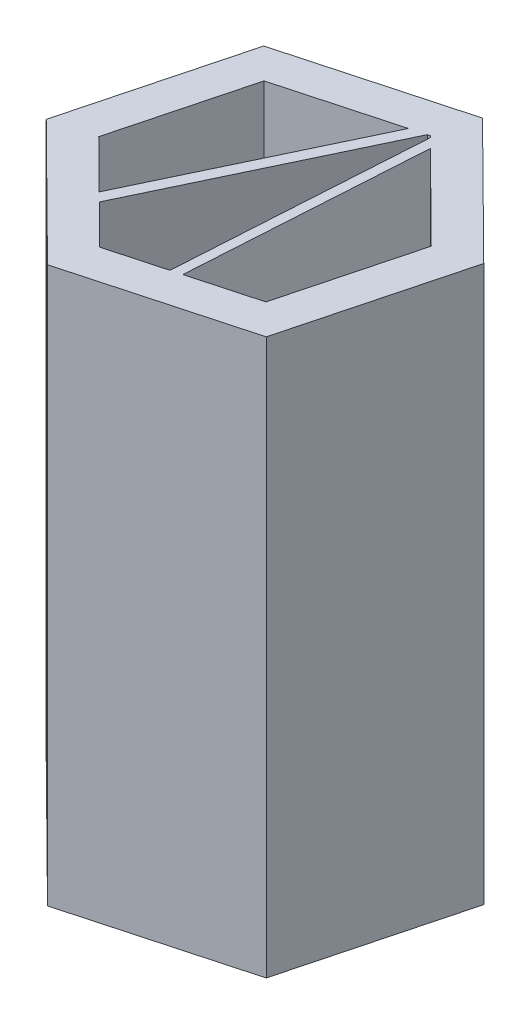
SolidWorks part; units mm, degrees
ref_plane "Front Plane" through (0, 0, 0) normal (0, 0, 1) x (1, 0, 0)
ref_plane "Top Plane" through (0, 0, 0) normal (0, 1, 0) x (1, 0, 0)
ref_plane "Right Plane" through (0, 0, 0) normal (1, 0, 0) x (0, 0, -1)
sketch "Sketch1" plane through (0, 0, 0) normal (0, 1, 0) x (1, 0, 0)
  line L1 (10.2574, -10.1548) -> (13.923, 3.8057)
  line L2 (13.923, 3.8057) -> (3.6656, 13.9605)
  line L3 (3.6656, 13.9605) -> (-10.2574, 10.1548)
  line L4 (-10.2574, 10.1548) -> (-13.923, -3.8057)
  line L5 (-13.923, -3.8057) -> (-3.6656, -13.9605)
  line L6 (-3.6656, -13.9605) -> (10.2574, -10.1548)
  line L7 (-2.7859, -10.61) -> (7.7956, -7.7176)
  line L8 (7.7956, -7.7176) -> (10.5815, 2.8924)
  line L9 (10.5815, 2.8924) -> (2.7859, 10.61)
  line L10 (2.7859, 10.61) -> (-7.7956, 7.7176)
  line L11 (-7.7956, 7.7176) -> (-10.5815, -2.8924)
  line L12 (-10.5815, -2.8924) -> (-2.7859, -10.61)
  circle A0 centre (0, 0) radius 12.5 construction
  circle A1 centre (0, 0) radius 9.5 construction
  dimension "D1" = 25
  dimension "D2" = 3
extrude "Boss-Extrude1" add sketch "Sketch1" along normal blind 45
sketch "Sketch2" plane through (0, 45, 0) normal (0, 1, 0) x (1, 0, 0)
  line L0 (-6.6837, -6.7512) -> (1.3912, 10.2288)
  line L1 (-10.5815, -2.8924) -> (-2.7859, -10.61) construction
  line L2 (2.7859, 10.61) -> (-7.7956, 7.7176) construction
  line L3 (1.3912, 10.2288) -> (2.593, 10.5573)
  line L4 (2.593, 10.5573) -> (-5.9728, -7.4549)
  line L5 (-5.9728, -7.4549) -> (-6.6837, -6.7512)
  line L6 (2.5049, -9.1638) -> (3.6844, 9.7204)
  line L7 (-2.7859, -10.61) -> (7.7956, -7.7176) construction
  line L8 (10.5815, 2.8924) -> (2.7859, 10.61) construction
  line L9 (3.6844, 9.7204) -> (2.928, 10.4693)
  line L10 (2.928, 10.4693) -> (1.6877, -9.3872)
  line L11 (1.6877, -9.3872) -> (2.5049, -9.1638)
  dimension "D1" = 0.2
  dimension "D2" = 0.2
extrude "Boss-Extrude2" add sketch "Sketch2" against normal blind 45
